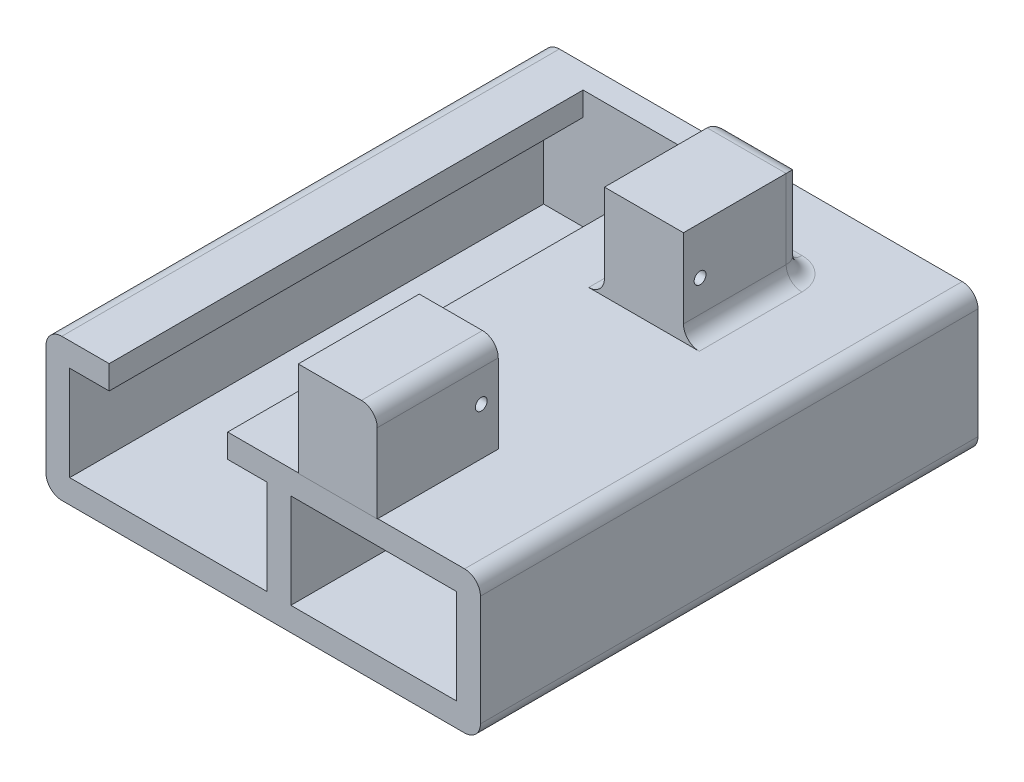
SolidWorks part; units mm, degrees
ref_plane "Front Plane" through (0, 0, 0) normal (0, 0, 1) x (1, 0, 0)
ref_plane "Top Plane" through (0, 0, 0) normal (0, 1, 0) x (1, 0, 0)
ref_plane "Right Plane" through (0, 0, 0) normal (1, 0, 0) x (0, 0, -1)
sketch "Sketch1" plane through (0, 0, 0) normal (0, 0, 1) x (1, 0, 0)
  line L0 (17.5093, 21.5886) -> (-9.4907, 21.5886)
  line L5 (-9.4907, 18.5886) -> (-9.4907, 6.5886)
  line L6 (-9.4907, 6.5886) -> (-34.4907, 6.5886)
  line L7 (-34.4907, 6.5886) -> (-34.4907, 18.5886)
  line L8 (-34.4907, 21.5886) -> (-37.4907, 21.5886)
  line L9 (-37.4907, 21.5886) -> (-37.4907, 3.5886)
  line L10 (-37.4907, 3.5886) -> (17.5093, 3.5886)
  line L11 (17.5093, 3.5886) -> (17.5093, 21.5886)
  line L14 (14.5093, 18.5886) -> (-6.4907, 18.5886)
  line L15 (14.5093, 18.5886) -> (14.5093, 6.5886)
  line L16 (14.5093, 6.5886) -> (-6.4907, 6.5886)
  line L17 (-6.4907, 18.5886) -> (-6.4907, 6.5886)
  line L18 (-9.4907, 21.5886) -> (-14.4907, 21.5886)
  line L20 (-9.4907, 18.5886) -> (-14.4907, 18.5886)
  line L21 (-14.4907, 21.5886) -> (-14.4907, 18.5886)
  line L22 (-34.4907, 21.5886) -> (-29.4907, 21.5886)
  line L24 (-34.4907, 18.5886) -> (-29.4907, 18.5886)
  line L25 (-29.4907, 21.5886) -> (-29.4907, 18.5886)
  dimension "D2" = 25
  dimension "D3" = 3
  dimension "D4" = 55
  dimension "D5" = 3
  dimension "D6" = 15
  dimension "D7" = 3
  dimension "D8" = 3
  dimension "D9" = 3
  dimension "D10" = 3
  dimension "D11" = 3
  dimension "D12" = 3
  dimension "D13" = 5
  dimension "D14" = 5
extrude "Boss-Extrude1" add sketch "Sketch1" against normal blind 60
ref_plane "Plane1" through (-5.4907, 0, 0) normal (-1, 0, 0) x (0, 0, 1)
sketch "Sketch2" plane through (-5.4907, 0, 0) normal (-1, 0, 0) x (0, 0, 1)
  line L5 (-38.7098, 21.5886) -> (-38.7098, 33.5886)
  line L11 (-60, 21.5886) -> (0, 21.5886) construction
  line L14 (-38.7098, 33.5886) -> (-53.7098, 33.5886)
  line L15 (-53.7098, 33.5886) -> (-53.7098, 21.5886)
  line L16 (-53.7098, 21.5886) -> (-38.7098, 21.5886)
  line L17 (-15.2598, 21.5886) -> (-15.2598, 33.5886)
  line L18 (-15.2598, 33.5886) -> (0.0607, 33.5886)
  line L19 (0.0607, 33.5886) -> (0.0607, 21.5886)
  line L20 (0.0607, 21.5886) -> (-15.2598, 21.5886)
  line L21 (-15.4598, 33.2886) -> (-15.4598, 21.8886) construction
  line L22 (-38.5098, 21.8886) -> (-38.5098, 33.2886) construction
  circle A4 centre (-40.8098, 27.5886) radius 0.75
  circle A5 centre (-13.1098, 27.5886) radius 0.75
  dimension "D2" = 12
  dimension "D4" = 0.2
  dimension "D5" = 15
  dimension "D6" = 1.5
  dimension "D7" = 1.5
  dimension "D1" = 12
  dimension "D3" = 0.2
extrude "Boss-Extrude2" add sketch "Sketch2" against normal blind 10
sketch "Sketch3" plane through (0, 0, -60) normal (0, 0, -1) x (-1, 0, 0)
  line L1 (-17.5093, 21.5886) -> (37.4907, 21.5886)
  line L2 (-17.5093, 21.5886) -> (-17.5093, 3.5886)
  line L3 (-17.5093, 3.5886) -> (37.4907, 3.5886)
  line L4 (37.4907, 21.5886) -> (37.4907, 3.5886)
extrude "Boss-Extrude3" add sketch "Sketch3" along normal blind 3
fillet "Fillet1" radius 2 11 edges at (17.5093, 21.5886, -31.5) (17.5093, 3.5886, -31.5) (-37.4907, 3.5886, -31.5) (-37.4907, 21.5886, -31.5) (-5.4907, 21.5886, -46.2098) (4.5093, 33.5886, -7.5996) (4.5093, 27.5886, -53.7098) (-5.4907, 27.5886, -53.7098) (-0.4907, 33.5886, -53.7098) (4.5093, 21.5886, -46.2098) (-0.4907, 21.5886, -53.7098)
